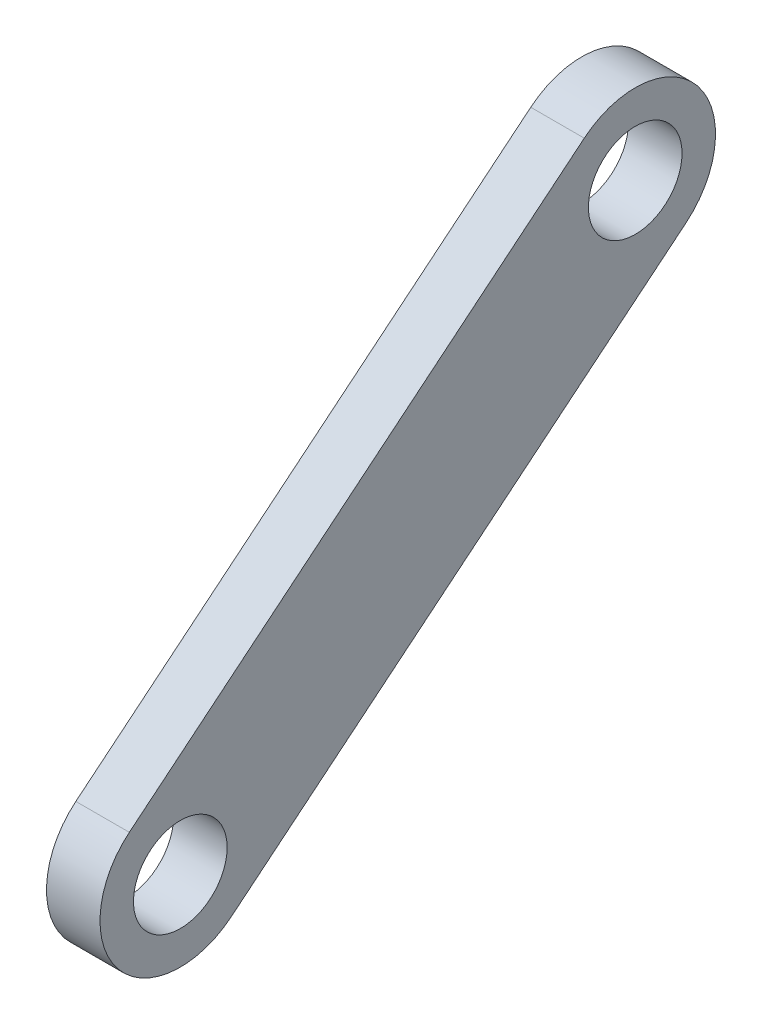
SolidWorks part; units mm, degrees
ref_plane "Front Plane" through (0, 0, 0) normal (0, 0, 1) x (1, 0, 0)
ref_plane "Top Plane" through (0, 0, 0) normal (0, 1, 0) x (1, 0, 0)
ref_plane "Right Plane" through (0, 0, 0) normal (1, 0, 0) x (0, 0, -1)
sketch "Sketch1" plane through (0, 0, 0) normal (1, 0, 0) x (0, 0, -1)
  line L0 (0, 0) -> (215.9, 0) construction
  line L1 (0, 0) -> (0, 139.7) construction
  line L2 (215.9, 139.7) -> (0, 0) construction
  line L3 (107.95, 0) -> (107.95, 183.1731) construction
  line L4 (107.95, 0) -> (107.95, -157.3657) construction
  line L5 (215.9, 0) -> (215.9, 139.7) construction
  line L6 (0, 0) -> (107.95, 88.6729)
  line L7 (215.9, 0) -> (107.95, 88.6729)
  line L8 (0, 0) -> (107.95, -88.6729)
  line L9 (215.9, 0) -> (107.95, -88.6729)
  line L10 (0, 0) -> (107.95, 88.6729) construction
  line L11 (-12.0918, 14.7205) -> (95.8582, 103.3934)
  line L12 (12.0918, -14.7205) -> (120.0418, 73.9525)
  circle A0 centre (0, 0) radius 11.1125
  circle A1 centre (107.95, 88.6729) radius 11.1125
  arc A2 (-12.0918, 14.7205) -> (12.0918, -14.7205) centre (0, 0) ccw
  arc A3 (120.0418, 73.9525) -> (95.8582, 103.3934) centre (107.95, 88.6729) ccw
  point P12 (53.975, 44.3365)
  dimension "D4" = 22.225
  dimension "D5" = 22.225
  dimension "D6" = 19.05
  dimension "D1" = 215.9
  dimension "D2" = 139.7
  dimension "D3" = 139.7
extrude "Boss-Extrude1" add sketch "Sketch1" along normal blind 12.7 contours L7 A3 L11 A2 L12 L8 A0 L6 A1 | L12 A3 L7 A1 L6 A0 L8
